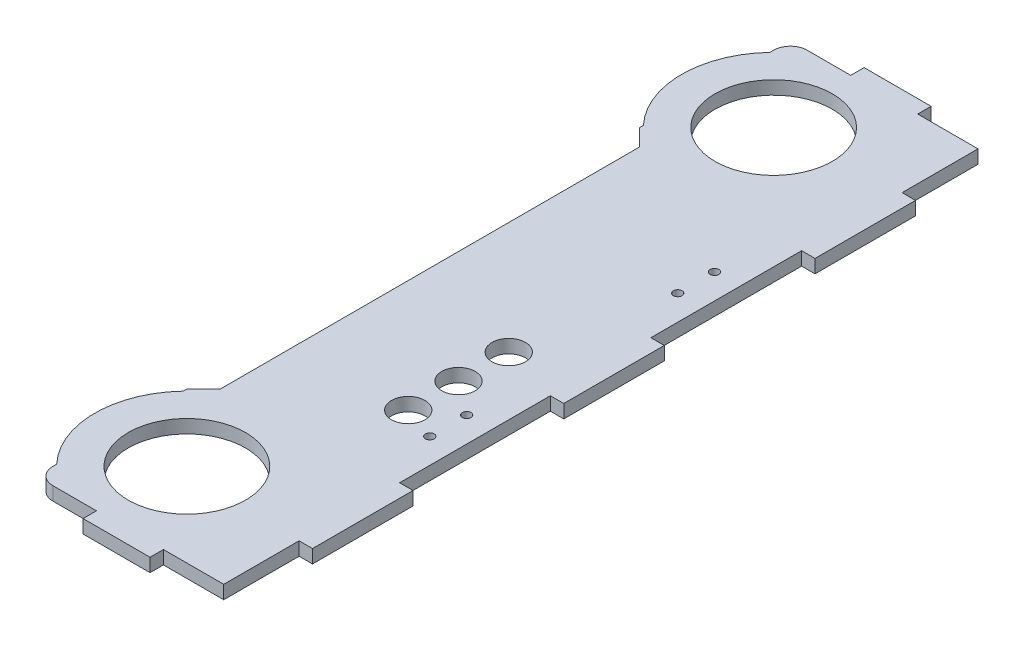
SolidWorks part; units mm, degrees
material "PMMA"
ref_plane "Plan de face" through (0, 0, 0) normal (0, 0, 1) x (1, 0, 0)
ref_plane "Plan de dessus" through (0, 0, 0) normal (0, 1, 0) x (1, 0, 0)
ref_plane "Plan de droite" through (0, 0, 0) normal (1, 0, 0) x (0, 0, -1)
sketch "Esquisse1" plane through (0, 0, 0) normal (0, 0, 1) x (1, 0, 0)
  line L0 (-148, -56) -> (-148, -48)
  line L1 (-148, -48) -> (-36, -48)
  line L2 (-36, -48) -> (-36, -56)
  line L4 (-36, -56) -> (-148, -56)
  line L5 (-115, -43.4904) -> (83.4562, -43.4904) construction
  line L10 (-36, -56) -> (-36, -44) construction
  line L11 (-36, -56) -> (-28, -56) construction
  dimension "D1" = 112
  dimension "D2" = 8
extrude "Boss.-Extru.1" add sketch "Esquisse1" along normal up to surface (450.3 mm away)
sketch "Esquisse2" plane through (0, -56, 0) normal (0, -1, 0) x (1, 0, 0)
  line L1 (-148, 450.3) -> (-148, 0) construction
  line L2 (-148, 360.15) -> (-138, 350.15)
  line L3 (-138, 350.15) -> (-138, 100.15)
  line L4 (-138, 100.15) -> (-148, 90.15)
  line L5 (-148, 90.15) -> (-148, 360.15)
  line L6 (-36, 450.3) -> (-36, 0) construction
  point P8 (-138, 225.15)
  point P13 (-36, 225.15)
  dimension "D1" = 270
  dimension "D2" = 10
  dimension "D3" = 10
  dimension "D4" = 10
extrude "Enlèv. mat.-Extru.1" cut sketch "Esquisse2" against normal blind 10
sketch "Esquisse3" plane through (0, -56, 0) normal (0, -1, 0) x (1, 0, 0)
  line L0 (-148, 450.3) -> (-36, 450.3) construction
  line L1 (-72, 450.3) -> (-112, 450.3)
  line L2 (-72, 450.3) -> (-72, 458.3)
  line L3 (-72, 458.3) -> (-112, 458.3)
  line L4 (-112, 450.3) -> (-112, 458.3)
  line L5 (-26.5, 458.3) -> (64, 458.3) construction
  line L7 (-148, 450.3) -> (-148, 360.15) construction
  line L8 (-148, 0) -> (-36, 0) construction
  line L9 (-72, 0) -> (-112, 0)
  line L10 (-72, 0) -> (-72, -8)
  line L11 (-72, -8) -> (-112, -8)
  line L12 (-112, 0) -> (-112, -8)
  line L13 (64, -8) -> (-26.5, -8) construction
  line L15 (-148, 90.15) -> (-148, 0) construction
  point P10 (-92, 458.3)
  point P22 (-92, -8)
  dimension "D1" = 40
  dimension "D2" = 56
  dimension "D3" = 40
  dimension "D4" = 56
extrude "Boss.-Extru.2" add sketch "Esquisse3" against normal blind 8
sketch "Esquisse4" plane through (0, -48, 0) normal (0, 1, 0) x (1, 0, 0)
  line L0 (-36, 0) -> (-72, 0) construction
  line L1 (-148, -90.15) -> (-148, 0) construction
  line L2 (-148, -450.3) -> (-148, -360.15) construction
  line L3 (-36, -450.3) -> (-72, -450.3) construction
  circle A0 centre (-108, -50) radius 35
  circle A1 centre (-108, -400.3) radius 35
  dimension "D1" = 70
  dimension "D2" = 50
  dimension "D3" = 40
  dimension "D4" = 40
  dimension "D5" = 50
  dimension "D6" = 70
extrude "Enlèv. mat.-Extru.2" cut sketch "Esquisse4" against normal blind 10
sketch "Esquisse5" plane through (0, -56, 0) normal (0, -1, 0) x (1, 0, 0)
  line L0 (-36, 450.3) -> (-36, 0) construction
  line L1 (-36, 255.3) -> (-28, 255.3)
  line L2 (-36, 255.3) -> (-36, 195.3)
  line L3 (-36, 195.3) -> (-28, 195.3)
  line L4 (-28, 255.3) -> (-28, 195.3)
  line L5 (-28, 450.3) -> (-28, 405.3) construction
  line L6 (-28, 450.3) -> (-36, 450.3) construction
  line L8 (-28, 405.3) -> (-36, 405.3)
  line L9 (-28, 405.3) -> (-28, 345.3)
  line L10 (-28, 345.3) -> (-36, 345.3)
  line L11 (-36, 405.3) -> (-36, 345.3)
  line L12 (-36, 105.3) -> (-28, 105.3)
  line L13 (-36, 105.3) -> (-36, 45.3)
  line L14 (-36, 45.3) -> (-28, 45.3)
  line L15 (-28, 105.3) -> (-28, 45.3)
  point P10 (-32, 450.3)
  dimension "D1" = 60
  dimension "D2" = 195
  dimension "D3" = 90
  dimension "D4" = 60
  dimension "D5" = 60
  dimension "D6" = 90
extrude "Boss.-Extru.3" add sketch "Esquisse5" against normal blind 8
sketch "Esquisse7" plane through (0, -56, 0) normal (0, -1, 0) x (1, 0, 0)
  line L0 (-148, 438.0492) -> (-148, 362.5508)
  line L1 (-148, 12.2508) -> (-148, 87.7492)
  line L2 (-148, 450.3) -> (-112, 450.3) construction
  line L3 (-148, 0) -> (-112, 0) construction
  circle A2 centre (-108, 400.3) radius 55
  arc A3 (-148, 438.0492) -> (-148, 362.5508) centre (-108, 400.3) ccw
  circle A5 centre (-108, 50) radius 55
  arc A6 (-148, 87.7492) -> (-148, 12.2508) centre (-108, 50) ccw
  dimension "D3" = 12.2508
  dimension "D4" = 12.2508
  dimension "D1" = 20
  dimension "D2" = 20
extrude "Boss.-Extru.5" add sketch "Esquisse7" against normal blind 8
fillet "Congé1" radius 10 2 edges at (-148, -52, 0) (-148, -52, 450.3)
sketch "Esquisse8" plane through (0, -48, 0) normal (0, 1, 0) x (1, 0, 0)
  line L0 (-48.3, -292.8) -> (-48.3, -287.8) construction
  line L1 (-53.7, -287.8) -> (-53.7, -292.8) construction
  line L2 (-48.3, -314.8) -> (-48.3, -309.8) construction
  line L3 (-53.7, -309.8) -> (-53.7, -314.8) construction
  line L4 (-53.7, -139.8) -> (-53.7, -144.8) construction
  line L5 (-48.3, -144.8) -> (-48.3, -139.8) construction
  line L6 (-48.3, -166.8) -> (-48.3, -161.8) construction
  line L7 (-53.7, -161.8) -> (-53.7, -166.8) construction
  line L8 (-48.3, -292.8) -> (-48.3, -287.8) construction
  line L9 (-53.7, -287.8) -> (-53.7, -292.8) construction
  line L10 (-48.3, -314.8) -> (-48.3, -309.8) construction
  line L11 (-53.7, -309.8) -> (-53.7, -314.8) construction
  line L12 (-53.7, -139.8) -> (-53.7, -144.8) construction
  line L13 (-48.3, -144.8) -> (-48.3, -139.8) construction
  line L14 (-48.3, -166.8) -> (-48.3, -161.8) construction
  line L15 (-53.7, -161.8) -> (-53.7, -166.8) construction
  line L16 (-51, -314.8) -> (-51, -309.8) construction
  line L17 (-51, -292.8) -> (-51, -287.8) construction
  line L18 (-51, -166.8) -> (-51, -161.8) construction
  line L19 (-51, -144.8) -> (-51, -139.8) construction
  arc A0 (-48.3, -287.8) -> (-53.7, -287.8) centre (-51, -287.8) ccw construction
  arc A1 (-53.7, -292.8) -> (-48.3, -292.8) centre (-51, -292.8) ccw construction
  arc A2 (-48.3, -309.8) -> (-53.7, -309.8) centre (-51, -309.8) ccw construction
  arc A3 (-53.7, -314.8) -> (-48.3, -314.8) centre (-51, -314.8) ccw construction
  arc A4 (-48.3, -139.8) -> (-53.7, -139.8) centre (-51, -139.8) ccw construction
  arc A5 (-53.7, -144.8) -> (-48.3, -144.8) centre (-51, -144.8) ccw construction
  arc A6 (-53.7, -166.8) -> (-48.3, -166.8) centre (-51, -166.8) ccw construction
  arc A7 (-48.3, -161.8) -> (-53.7, -161.8) centre (-51, -161.8) ccw construction
  arc A8 (-48.3, -287.8) -> (-53.7, -287.8) centre (-51, -287.8) ccw construction
  arc A9 (-53.7, -292.8) -> (-48.3, -292.8) centre (-51, -292.8) ccw construction
  arc A10 (-48.3, -309.8) -> (-53.7, -309.8) centre (-51, -309.8) ccw construction
  arc A11 (-53.7, -314.8) -> (-48.3, -314.8) centre (-51, -314.8) ccw construction
  arc A12 (-48.3, -139.8) -> (-53.7, -139.8) centre (-51, -139.8) ccw construction
  arc A13 (-53.7, -144.8) -> (-48.3, -144.8) centre (-51, -144.8) ccw construction
  arc A14 (-53.7, -166.8) -> (-48.3, -166.8) centre (-51, -166.8) ccw construction
  arc A15 (-48.3, -161.8) -> (-53.7, -161.8) centre (-51, -161.8) ccw construction
  circle A16 centre (-51, -142.3) radius 2.6
  circle A17 centre (-51, -164.3) radius 2.6
  circle A18 centre (-51, -312.3) radius 2.6
  circle A19 centre (-51, -290.3) radius 2.6
  dimension "D1" = 5.2
  dimension "D2" = 5.2
  dimension "D3" = 5.2
  dimension "D4" = 5.2
extrude "Enlèv. mat.-Extru.3" cut sketch "Esquisse8" against normal blind 8
sketch "Esquisse9" plane through (0, -56, 0) normal (0, -1, 0) x (1, 0, 0)
  circle A0 centre (-71, 305.15) radius 10 construction
  circle A1 centre (-71, 275.15) radius 10 construction
  circle A2 centre (-71, 245.15) radius 10 construction
  circle A3 centre (-71, 305.15) radius 10
  circle A4 centre (-71, 275.15) radius 10
  circle A5 centre (-71, 245.15) radius 10
extrude "Enlèv. mat.-Extru.4" cut sketch "Esquisse9" against normal blind 10
